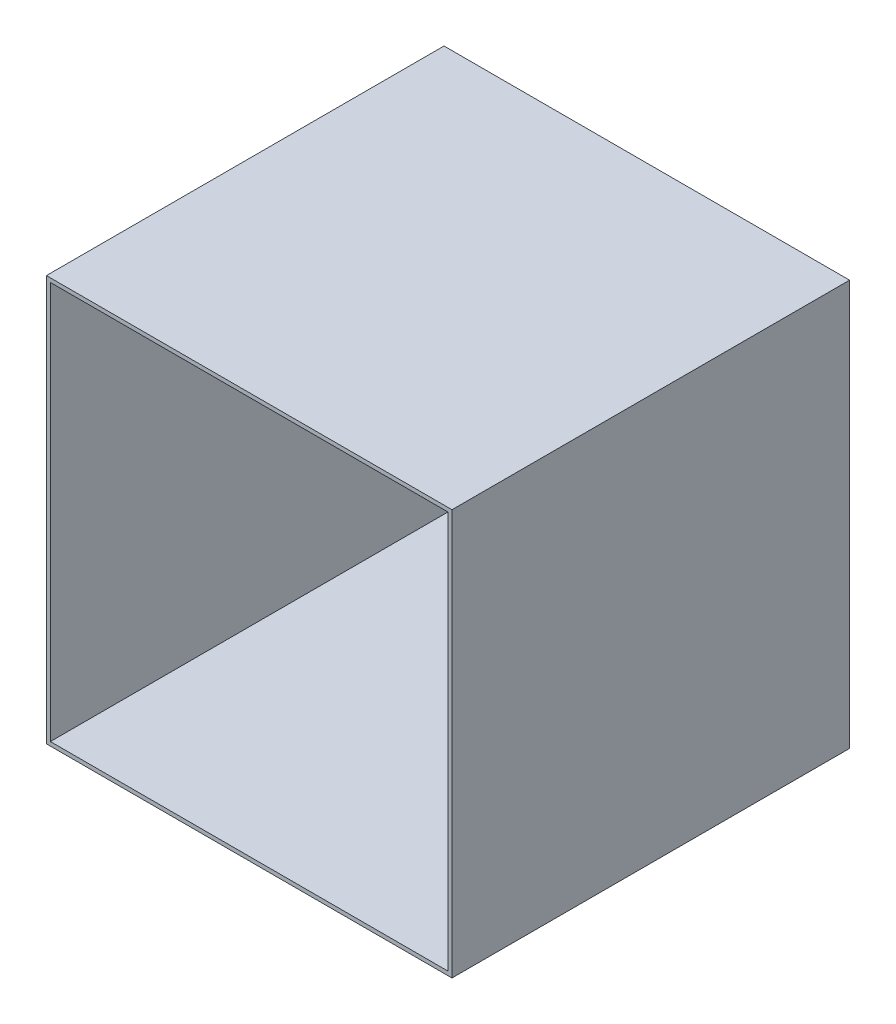
SolidWorks part; units mm, degrees
ref_plane "Спереди" through (0, 0, 0) normal (0, 0, 1) x (1, 0, 0)
ref_plane "Сверху" through (0, 0, 0) normal (0, 1, 0) x (1, 0, 0)
ref_plane "Справа" through (0, 0, 0) normal (1, 0, 0) x (0, 0, -1)
sketch "Эскиз1" plane through (0, 0, 0) normal (0, 0, 1) x (1, 0, 0)
  line L1 (-104.1565, 121.1782) -> (95.8435, 121.1782)
  line L2 (-104.1565, 121.1782) -> (-104.1565, -78.8218)
  line L3 (-104.1565, -78.8218) -> (95.8435, -78.8218)
  line L4 (95.8435, 121.1782) -> (95.8435, -78.8218)
  dimension "D1" = 200
  dimension "D2" = 200
extrude "Вытянуть-Тонкостенный1" add sketch "Эскиз1" along normal blind 200 thin thin type one direction wall 2
